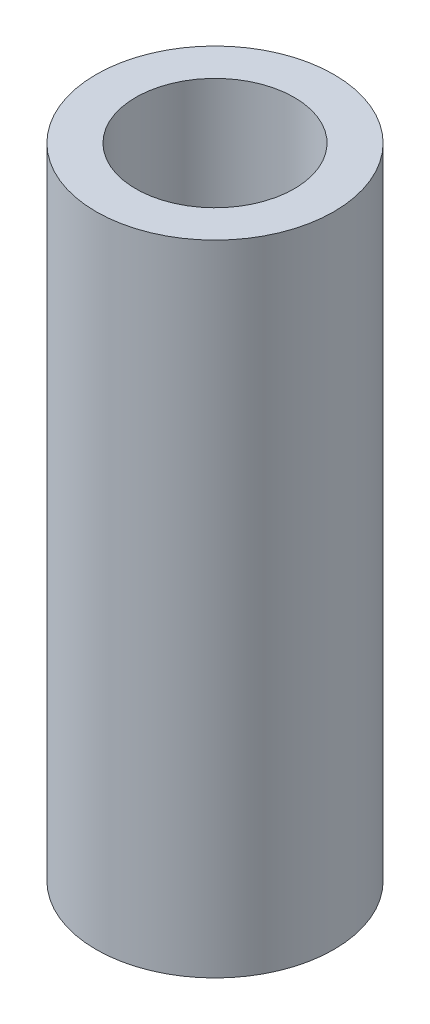
SolidWorks part; units mm, degrees
ref_plane "Спереди" through (0, 0, 0) normal (0, 0, 1) x (1, 0, 0)
ref_plane "Сверху" through (0, 0, 0) normal (0, 1, 0) x (1, 0, 0)
ref_plane "Справа" through (0, 0, 0) normal (1, 0, 0) x (0, 0, -1)
sketch "Эскиз1" plane through (0, 0, 0) normal (0, 1, 0) x (1, 0, 0)
  circle A0 centre (0, 0) radius 1.6
  circle A1 centre (0, 0) radius 2.4
  dimension "D1" = 3.2
  dimension "D2" = 4.8
extrude "Бобышка-Вытянуть1" add sketch "Эскиз1" along normal blind 12.9
